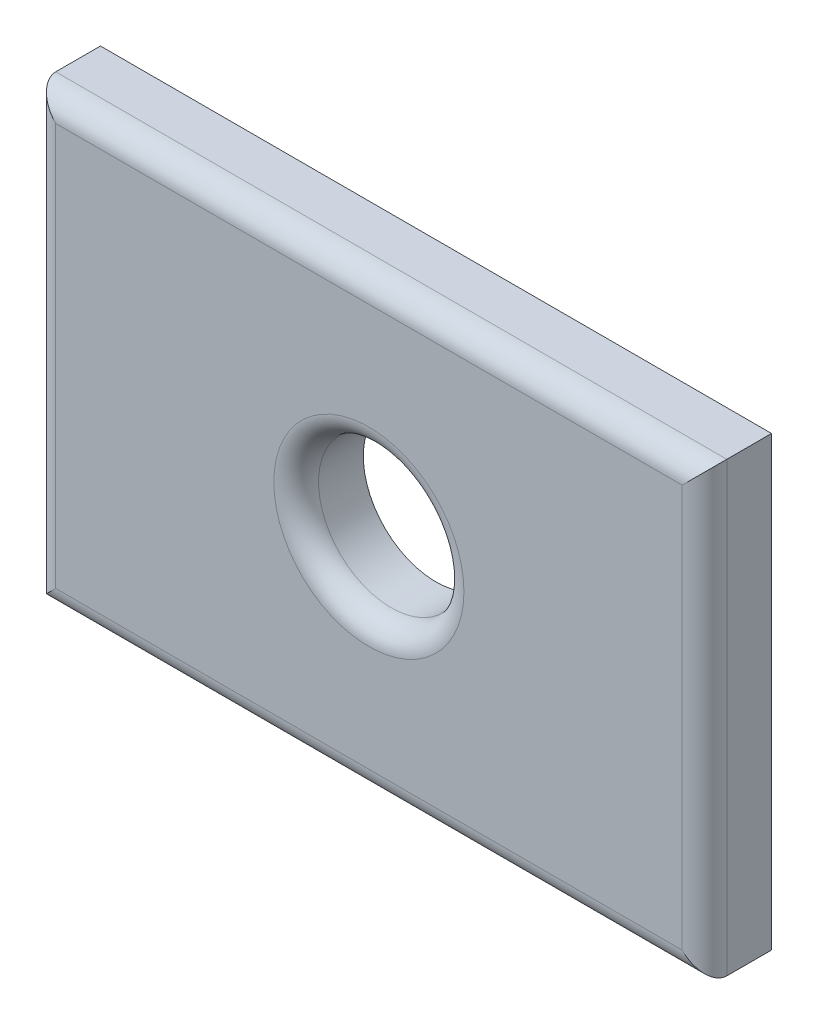
SolidWorks part; units mm, degrees
material "ABS"
ref_plane "Plan de face" through (0, 0, 0) normal (0, 0, 1) x (1, 0, 0)
ref_plane "Plan de dessus" through (0, 0, 0) normal (0, 1, 0) x (1, 0, 0)
ref_plane "Plan de droite" through (0, 0, 0) normal (1, 0, 0) x (0, 0, -1)
sketch "Esquisse1" plane through (0, 0, 0) normal (0, 0, 1) x (1, 0, 0)
  line L1 (-20.0778, 9.0261) -> (9.9222, 9.0261)
  line L2 (-20.0778, 9.0261) -> (-20.0778, -10.9739)
  line L3 (-20.0778, -10.9739) -> (9.9222, -10.9739)
  line L4 (9.9222, 9.0261) -> (9.9222, -10.9739)
  dimension "D1" = 20
  dimension "D2" = 30
extrude "Boss.-Extru.1" add sketch "Esquisse1" along normal blind 3
sketch "Esquisse2" plane through (0, 0, 3) normal (0, 0, 1) x (1, 0, 0)
  line L0 (-20.0778, 9.0261) -> (9.9222, -10.9739) construction
  circle A0 centre (-5.0778, -0.9739) radius 3.25
  dimension "D1" = 6.5
extrude "Enlèv. mat.-Extru.1" cut sketch "Esquisse2" against normal blind 3
fillet "Congé1" radius 1 5 edges at (-5.0778, 9.0261, 3) (9.9222, -0.9739, 3) (-5.0778, -10.9739, 3) (-20.0778, -0.9739, 3) (-1.8278, -0.9739, 3)
